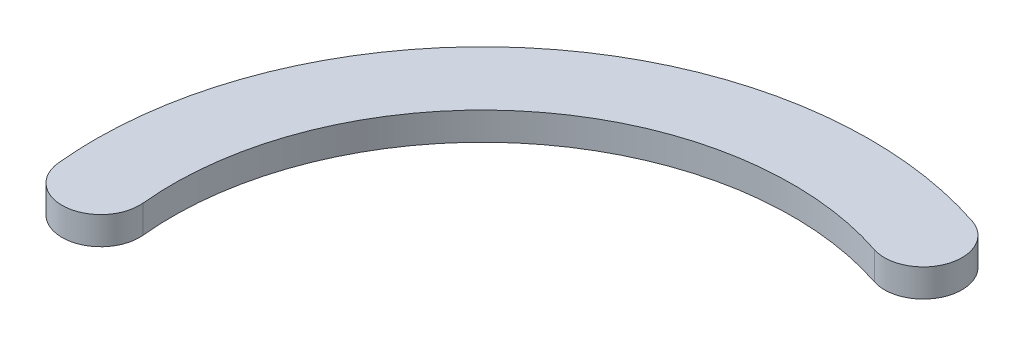
SolidWorks part; units mm, degrees
material "Perspex (TM) GS Acrylic Cast Sheet"
ref_plane "Front Plane" through (0, 0, 0) normal (0, 0, 1) x (1, 0, 0)
ref_plane "Top Plane" through (0, 0, 0) normal (0, 1, 0) x (1, 0, 0)
ref_plane "Right Plane" through (0, 0, 0) normal (1, 0, 0) x (0, 0, -1)
sketch "Sketch1" plane through (0, 0, 0) normal (0, 1, 0) x (1, 0, 0)
  arc A0 (-26.2849, -31.298) -> (47.3718, 27.7317) centre (29.6823, -25.6644) cw construction
  arc A1 (49.3373, 33.6646) -> (-32.5035, -31.924) centre (29.6823, -25.6644) ccw
  arc A2 (45.4063, 21.7988) -> (-20.0663, -30.6721) centre (29.6823, -25.6644) ccw
  arc A3 (45.4063, 21.7988) -> (49.3373, 33.6646) centre (47.3718, 27.7317) ccw
  arc A4 (-32.5035, -31.924) -> (-20.0663, -30.6721) centre (-26.2849, -31.298) ccw
  point P3 (-5.4948, 18.2291)
  point P9 (0, 0)
  point P10 (0, 0)
  point P11 (0, 0)
  point P12 (0, 0)
  point P13 (-26.2849, -31.298)
  dimension "D1" = 50
  dimension "D2" = 6.25
extrude "Boss-Extrude1" add sketch "Sketch1" along normal blind 4.5
sketch "Sketch2" plane through (0, 4.5, 0) normal (0, 1, 0) x (1, 0, 0)
  circle A0 centre (46.5766, 27.9886) radius 3.125
  arc A1 (45.4063, 21.7988) -> (-20.0663, -30.6721) centre (29.6823, -25.6644) ccw construction
  dimension "D1" = 6.25
  dimension "D2" = 56.25
sketch "Sketch3" plane through (0, 0, 0) normal (0, -1, 0) x (1, 0, 0)
  circle A0 centre (46.5766, -27.9886) radius 3.125
sketch "Sketch4" plane through (0, 4.5, 0) normal (0, 1, 0) x (1, 0, 0)
  circle A0 centre (-26.2849, -31.298) radius 3.125
  dimension "D1" = 6.25
sketch "Sketch5" plane through (0, 0, 0) normal (0, -1, 0) x (1, 0, 0)
  circle A0 centre (-26.2849, 31.298) radius 3.125
